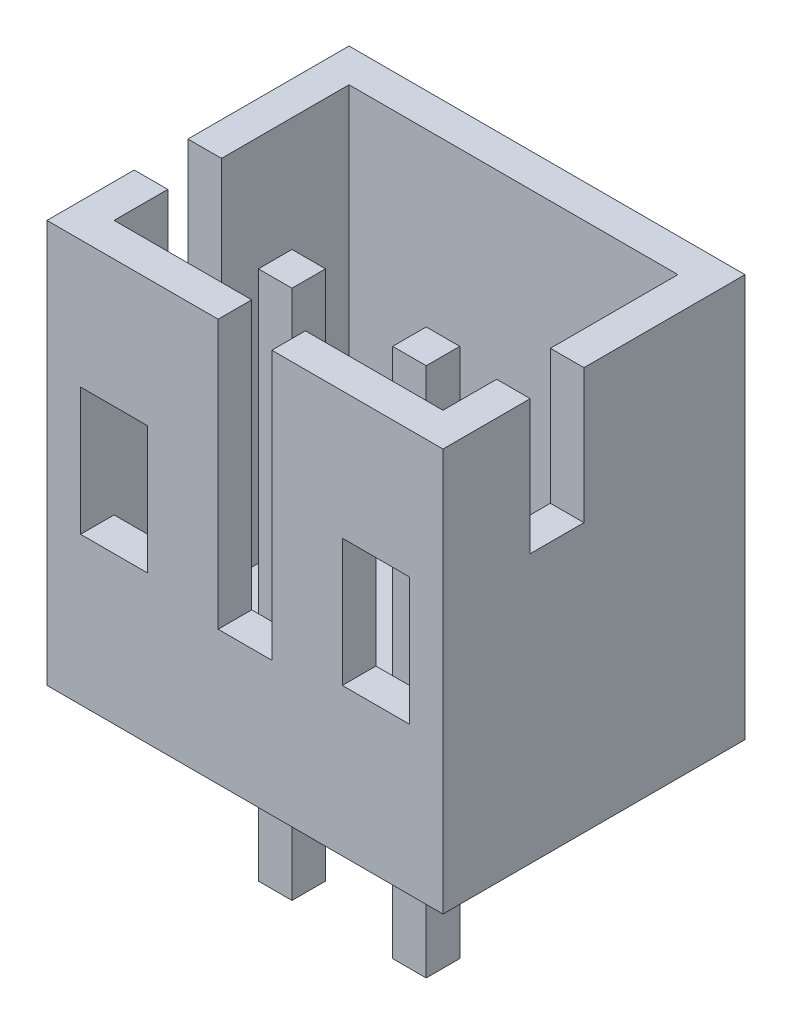
SolidWorks part; units mm, degrees
ref_plane "Front Plane" through (0, 0, 0) normal (0, 0, 1) x (1, 0, 0)
ref_plane "Top Plane" through (0, 0, 0) normal (0, 1, 0) x (1, 0, 0)
ref_plane "Right Plane" through (0, 0, 0) normal (1, 0, 0) x (0, 0, -1)
sketch "Sketch1" plane through (0, 0, 0) normal (0, 1, 0) x (1, 0, 0)
  line L0 (-2.95, -2.25) -> (2.95, -2.25)
  line L1 (-2.95, -2.25) -> (-2.95, 2.25)
  line L2 (2.95, -2.25) -> (2.95, 2.25)
  line L3 (-2.95, 2.25) -> (2.95, 2.25)
  line L4 (-2.95, -2.25) -> (2.95, 2.25) construction
  line L5 (2.95, -2.25) -> (-2.95, 2.25) construction
  point P1 (0, 0)
  dimension "D1" = 4.5
  dimension "D2" = 5.9
extrude "Boss-Extrude1" add sketch "Sketch1" along normal blind 6
sketch "Sketch2" plane through (0, 6, 0) normal (0, 1, 0) x (1, 0, 0)
  line L0 (-2.45, -1.75) -> (2.45, -1.75)
  line L1 (-2.45, -1.75) -> (-2.45, 1.75)
  line L2 (2.45, -1.75) -> (2.45, 1.75)
  line L3 (-2.45, 1.75) -> (2.45, 1.75)
  line L4 (-2.45, -1.75) -> (2.45, 1.75) construction
  line L5 (2.45, -1.75) -> (-2.45, 1.75) construction
  line L6 (2.95, 2.25) -> (-2.95, 2.25) construction
  line L7 (2.95, -2.25) -> (2.95, 2.25) construction
  point P1 (0, 0)
  dimension "D1" = 0.5
  dimension "D2" = 0.5
extrude "Cut-Extrude1" cut sketch "Sketch2" against normal blind 5.5
sketch "Sketch3" plane through (0, 0, 2.25) normal (0, 0, 1) x (1, 0, 0)
  line L0 (-2.45, 4.1) -> (-2.45, 2.2)
  line L1 (-2.45, 4.1) -> (-1.45, 4.1)
  line L2 (-2.45, 2.2) -> (-1.45, 2.2)
  line L3 (-1.45, 4.1) -> (-1.45, 2.2)
  line L4 (-2.45, 4.1) -> (-1.45, 2.2) construction
  line L5 (-2.45, 2.2) -> (-1.45, 4.1) construction
  line L6 (-2.95, 6) -> (2.95, 6) construction
  line L7 (-2.95, 6) -> (-2.95, 0) construction
  point P1 (-1.95, 3.15)
  dimension "D1" = 1
  dimension "D2" = 1.9
  dimension "D3" = 1.9
  dimension "D4" = 0.5
extrude "Cut-Extrude2" cut sketch "Sketch3" against normal up to surface (0.5 mm away) up to face at (0, 3.25, 1.75)
sketch "Sketch4" plane through (0, 0.5, 0) normal (0, 1, 0) x (1, 0, 0)
  line L0 (-1.25, -0.8) -> (-0.75, -0.8)
  line L1 (-1.25, -0.8) -> (-1.25, -0.3)
  line L2 (-0.75, -0.8) -> (-0.75, -0.3)
  line L3 (-1.25, -0.3) -> (-0.75, -0.3)
  line L4 (-1.25, -0.8) -> (-0.75, -0.3) construction
  line L5 (-0.75, -0.8) -> (-1.25, -0.3) construction
  line L6 (-2.95, -2.25) -> (2.95, -2.25) construction
  point P1 (-1, -0.55)
  dimension "D1" = 0.5
  dimension "D2" = 0.5
  dimension "D3" = 1.7
  dimension "D4" = 1
extrude "Boss-Extrude2" add sketch "Sketch4" along normal blind 5 and the other way blind 2.9
sketch "Sketch5" plane through (-2.95, 0, 0) normal (-1, 0, 0) x (0, 0, 1)
  line L0 (0.15, 4) -> (0.95, 4)
  line L1 (0.15, 4) -> (0.15, 6)
  line L2 (0.95, 4) -> (0.95, 6)
  line L3 (0.15, 6) -> (0.95, 6)
  line L4 (0.15, 4) -> (0.95, 6) construction
  line L5 (0.95, 4) -> (0.15, 6) construction
  line L6 (-2.25, 6) -> (2.25, 6) construction
  line L8 (2.25, 6) -> (2.25, 0) construction
  point P1 (0.55, 5)
  dimension "D1" = 0.8
  dimension "D2" = 2
  dimension "D3" = 1.7
extrude "Cut-Extrude3" cut sketch "Sketch5" against normal up to surface (0.5 mm away) up to face at (-2.45, 3.2, 1)
mirror "Mirror1" about plane through (0, 0, 0) normal (1, 0, 0) of "Cut-Extrude2", "Cut-Extrude3"
sketch "Sketch6" plane through (0, 0, 2.25) normal (0, 0, 1) x (1, 0, 0)
  line L0 (-0.4, 2) -> (0.4, 2)
  line L1 (-0.4, 2) -> (-0.4, 6)
  line L2 (0.4, 2) -> (0.4, 6)
  line L3 (-0.4, 6) -> (0.4, 6)
  line L4 (-0.4, 2) -> (0.4, 6) construction
  line L5 (0.4, 2) -> (-0.4, 6) construction
  line L6 (-2.95, 6) -> (2.95, 6) construction
  point P1 (0, 4)
  dimension "D1" = 0.8
  dimension "D2" = 4
  dimension "D3" = 0.4
extrude "Cut-Extrude4" cut sketch "Sketch6" against normal up to surface (0.5 mm away) up to face at (0, 3.1833, 1.75)
mirror "Mirror2" about plane through (0, 0, 0) normal (1, 0, 0) of "Boss-Extrude2"
